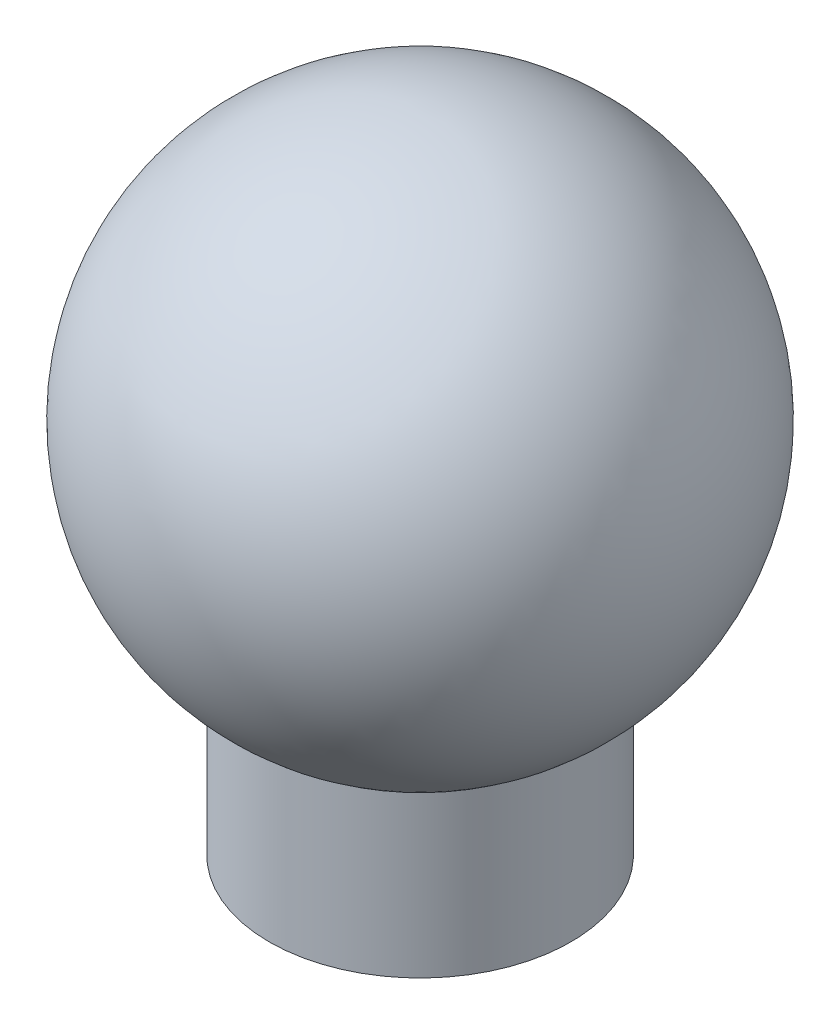
SolidWorks part; units mm, degrees
ref_plane "前视基准面" through (0, 0, 0) normal (0, 0, 1) x (1, 0, 0)
ref_plane "上视基准面" through (0, 0, 0) normal (0, 1, 0) x (1, 0, 0)
ref_plane "右视基准面" through (0, 0, 0) normal (1, 0, 0) x (0, 0, -1)
sketch "草图1" plane through (0, 0, 0) normal (0, 1, 0) x (1, 0, 0)
  circle A0 centre (0, 0) radius 4
extrude "凸台-拉伸1" add sketch "草图1" along normal blind 10
sketch "草图2" plane through (0, 10, 0) normal (0, 1, 0) x (1, 0, 0)
  line L0 (0, 7) -> (0, -7)
  arc A0 (0, -7) -> (0, 7) centre (0, 0) ccw
revolve "旋转1" add sketch "草图2" angle 360 about L0
sketch "草图3" plane through (0, 0, 0) normal (0, -1, 0) x (1, 0, 0)
  line L0 (0, 3.2) -> (-2.8792, -1.3965)
  arc A0 (-2.8792, -1.3965) -> (0, 3.2) centre (0, 0) ccw
extrude "切除-拉伸1" cut sketch "草图3" against normal blind 7
